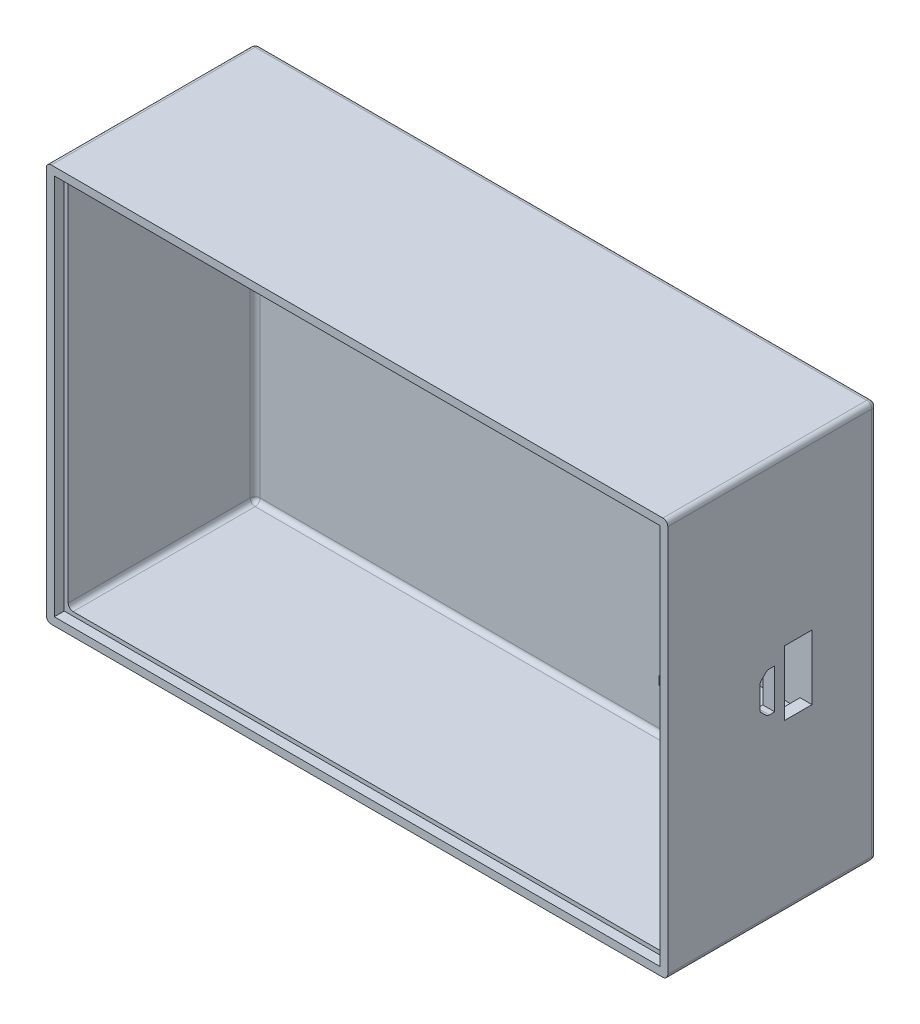
SolidWorks part; units mm, degrees
material "Резина"
ref_plane "Спереди" through (0, 0, 0) normal (0, 0, 1) x (1, 0, 0)
ref_plane "Сверху" through (0, 0, 0) normal (0, 1, 0) x (1, 0, 0)
ref_plane "Справа" through (0, 0, 0) normal (1, 0, 0) x (0, 0, -1)
sketch "Эскиз1" plane through (0, 0, 0) normal (0, 0, 1) x (1, 0, 0)
  line L1 (-62.5, 40) -> (62.5, 40)
  line L2 (-62.5, 40) -> (-62.5, -40)
  line L3 (-62.5, -40) -> (62.5, -40)
  line L4 (62.5, 40) -> (62.5, -40)
  line L5 (-62.5, 40) -> (62.5, -40) construction
  line L6 (-62.5, -40) -> (62.5, 40) construction
  point P0 (0, 0)
  dimension "D1" = 125
  dimension "D2" = 80
extrude "Бобышка-Вытянуть1" add sketch "Эскиз1" along normal blind 40
sketch "Эскиз2" plane through (0, 0, 40) normal (0, 0, 1) x (1, 0, 0)
  line L0 (62.5, 40) -> (-62.5, 40) construction
  line L1 (-60.1, 37.6) -> (60.1, 37.6)
  line L2 (-60.1, 37.6) -> (-60.1, -37.6)
  line L3 (-60.1, -37.6) -> (60.1, -37.6)
  line L4 (60.1, 37.6) -> (60.1, -37.6)
  line L5 (-60.1, 37.6) -> (60.1, -37.6) construction
  line L6 (-60.1, -37.6) -> (60.1, 37.6) construction
  line L7 (62.5, -40) -> (62.5, 40) construction
  point P0 (0, 0)
  dimension "D1" = 2.4
  dimension "D2" = 2.4
extrude "Вырез-Вытянуть1" cut sketch "Эскиз2" against normal blind 37.6
fillet "Скругление1" radius 1 8 edges at (62.5, -40, 20) (62.5, 40, 20) (62.5, 0, 0) (0, 40, 0) (-62.5, 40, 20) (-62.5, -40, 20) (0, -40, 0) (-62.5, 0, 0)
fillet "Скругление2" radius 1 8 edges at (60.1, 37.6, 21.2) (60.1, 0, 2.4) (60.1, -37.6, 21.2) (0, 37.6, 2.4) (-60.1, 37.6, 21.2) (0, -37.6, 2.4) (-60.1, -37.6, 21.2) (-60.1, 0, 2.4)
sketch "Эскиз3" plane through (0, 0, 0) normal (0, 0, -1) x (-1, 0, 0)
  line L0 (-61.5, 5) -> (59.5, 5) construction
  line L4 (-61.5, 39) -> (-61.5, -39) construction
  text T0 "Для\r\nЗСУ" font "Times New Roman" height 20
  dimension "D1" = 5
extrude "Вырез-Вытянуть2" cut sketch "Эскиз3" against normal blind 0.5
sketch "Эскиз4" plane through (62.5, 0, 0) normal (1, 0, 0) x (0, 0, -1)
  line L0 (0, 0) -> (-20.5, 0) construction
  line L1 (-20.5, -4) -> (-20.5, 4)
  line L2 (-20.5, 4) -> (-21.5858, 4)
  line L3 (-23.5, 2.0858) -> (-23.5, -2.0858)
  line L4 (-15.75, 0) -> (-20.5, 0) construction
  line L5 (-13, 6.5) -> (-18.5, 6.5)
  line L6 (-13, 6.5) -> (-13, -6.5)
  line L7 (-13, -6.5) -> (-18.5, -6.5)
  line L8 (-18.5, 6.5) -> (-18.5, -6.5)
  line L9 (-13, 6.5) -> (-18.5, -6.5) construction
  line L10 (-13, -6.5) -> (-18.5, 6.5) construction
  line L11 (-22.2929, 3.7071) -> (-23.2071, 2.7929)
  line L12 (-22.2929, -3.7071) -> (-23.2071, -2.7929)
  line L13 (-20.5, -4) -> (-21.5858, -4)
  arc A0 (-22.2929, -3.7071) -> (-21.5858, -4) centre (-21.5858, -3) ccw
  arc A1 (-23.2071, -2.7929) -> (-23.5, -2.0858) centre (-22.5, -2.0858) cw
  arc A2 (-23.2071, 2.7929) -> (-23.5, 2.0858) centre (-22.5, 2.0858) ccw
  arc A3 (-22.2929, 3.7071) -> (-21.5858, 4) centre (-21.5858, 3) cw
  point P5 (-15.75, 0)
  point P15 (-23.5, 0)
  point P18 (-22, -4)
  point P21 (-23.5, -2.5)
  point P24 (-23.5, 2.5)
  point P27 (-22, 4)
  dimension "D9" = 1
  dimension "D1" = 13
  dimension "D2" = 5.5
  dimension "D3" = 13
  dimension "D4" = 2
  dimension "D5" = 3
  dimension "D6" = 8
  dimension "D7" = 1.5
  dimension "D8" = 1.5
extrude "Вырез-Вытянуть3" cut sketch "Эскиз4" against normal blind 5
sketch "Эскиз5" plane through (60.1, 0, 0) normal (-1, 0, 0) x (0, 0, 1)
  line L0 (11.4, 0) -> (29.8169, 0) construction
  line L1 (11.4, 0) -> (11.4, -8.5)
  line L2 (11.4, -8.5) -> (13, -8.5)
  line L3 (13, -8.5) -> (13, 8.5)
  line L4 (11.4, 0) -> (11.4, 8.5)
  line L5 (11.4, 8.5) -> (13, 8.5)
  line L13 (0, -39) -> (0, 39) construction
  line L15 (11.4, -8.5) -> (21.4, -8.5)
  line L16 (11.4, -8.5) -> (11.4, -10.1)
  line L17 (11.4, -10.1) -> (21.4, -10.1)
  line L18 (21.4, -8.5) -> (21.4, -10.1)
  line L19 (11.4, -8.5) -> (21.4, -10.1) construction
  line L20 (11.4, -10.1) -> (21.4, -8.5) construction
  point P8 (16.4, -9.3)
  line M18 (18.5, 6.5) -> (18.5, -6.5)
  dimension "D1" = 1.6
  dimension "D2" = 17
  dimension "D3" = 8.5
  dimension "D4" = 13
  dimension "D5" = 17
  dimension "D6" = 1.6
  dimension "D7" = 10
  dimension "D8" = 11.4
extrude "Бобышка-Вытянуть2" add sketch "Эскиз5" along normal blind 20 contours L0 L1 L2 L3 M18 | L18 L15 L2 L16 L17
sketch "Эскиз6" plane through (0, 0, 13) normal (0, 0, 1) x (1, 0, 0)
  line L0 (40.1, 0) -> (43.5026, 0) construction
  line L1 (40.1, -8.5) -> (40.1, 8.5) construction
  line L2 (40.1, 8.5) -> (60.1, 8.5) construction
  line L3 (43.6526, -1.5) -> (43.3526, -1.5)
  line L4 (43.9026, -1.25) -> (43.9026, 1.25)
  line L5 (43.6526, 1.5) -> (43.3526, 1.5)
  line L6 (43.1026, -1.25) -> (43.1026, 1.25)
  line L7 (43.9026, -1.5) -> (43.1026, 1.5) construction
  line L8 (43.9026, 1.5) -> (43.1026, -1.5) construction
  line L9 (45.9832, 6.5) -> (43.9832, 6.5)
  line L10 (46.2332, 6.75) -> (46.2332, 7.05)
  line L11 (45.9832, 7.3) -> (43.9832, 7.3)
  line L12 (43.7332, 6.75) -> (43.7332, 7.05)
  line L13 (46.2332, 6.5) -> (43.7332, 7.3) construction
  line L14 (46.2332, 7.3) -> (43.7332, 6.5) construction
  arc A0 (43.9026, 1.25) -> (43.6526, 1.5) centre (43.6526, 1.25) ccw
  arc A1 (43.1026, 1.25) -> (43.3526, 1.5) centre (43.3526, 1.25) cw
  arc A2 (43.3526, -1.5) -> (43.1026, -1.25) centre (43.3526, -1.25) cw
  arc A3 (43.9026, -1.25) -> (43.6526, -1.5) centre (43.6526, -1.25) cw
  arc A4 (43.7332, 7.05) -> (43.9832, 7.3) centre (43.9832, 7.05) cw
  arc A5 (43.9832, 6.5) -> (43.7332, 6.75) centre (43.9832, 6.75) cw
  arc A6 (46.2332, 7.05) -> (45.9832, 7.3) centre (45.9832, 7.05) ccw
  arc A7 (46.2332, 6.75) -> (45.9832, 6.5) centre (45.9832, 6.75) cw
  point P8 (44.9832, 6.9)
  point P15 (44.9832, 7.3)
  dimension "D7" = 0.25
  dimension "D8" = 0.25
  dimension "D1" = 0.8
  dimension "D2" = 3
  dimension "D3" = 8.5
  dimension "D4" = 0.8
  dimension "D5" = 2.5
  dimension "D6" = 1.2
extrude "Бобышка-Вытянуть3" add sketch "Эскиз6" along normal blind 8
sketch "Эскиз7" plane through (0, 0, 40) normal (0, 0, 1) x (1, 0, 0)
  line L4 (60.9, -38.4) -> (60.9, 38.4)
  line L5 (60.9, 38.4) -> (-60.9, 38.4)
  line L6 (-60.9, 38.4) -> (-60.9, -38.4)
  line L7 (-60.9, -38.4) -> (60.9, -38.4)
  line L8 (-61.5, -40) -> (61.5, -40)
  line L9 (62.5, -39) -> (62.5, 39)
  line L10 (61.5, 40) -> (-61.5, 40)
  line L11 (-62.5, 39) -> (-62.5, -39)
  line L12 (-61.5, -40) -> (61.5, -40)
  line L13 (62.5, -39) -> (62.5, 39)
  line L14 (61.5, 40) -> (-61.5, 40)
  line L15 (-62.5, 39) -> (-62.5, -39)
  arc A4 (60.9, 38.4) -> (60.9, 38.4) centre (60.9, 38.4) ccw
  arc A5 (-60.9, 38.4) -> (-60.9, 38.4) centre (-60.9, 38.4) ccw
  arc A6 (-60.9, -38.4) -> (-60.9, -38.4) centre (-60.9, -38.4) ccw
  arc A7 (60.9, -38.4) -> (60.9, -38.4) centre (60.9, -38.4) ccw
  arc A8 (61.5, -40) -> (62.5, -39) centre (61.5, -39) ccw
  arc A9 (62.5, 39) -> (61.5, 40) centre (61.5, 39) ccw
  arc A10 (-61.5, 40) -> (-62.5, 39) centre (-61.5, 39) ccw
  arc A11 (-62.5, -39) -> (-61.5, -40) centre (-61.5, -39) ccw
  arc A12 (61.5, -40) -> (62.5, -39) centre (61.5, -39) ccw
  arc A13 (62.5, 39) -> (61.5, 40) centre (61.5, 39) ccw
  arc A14 (-61.5, 40) -> (-62.5, 39) centre (-61.5, 39) ccw
  arc A15 (-62.5, -39) -> (-61.5, -40) centre (-61.5, -39) ccw
  dimension "D1" = 0
  dimension "D2" = 1.6
extrude "Бобышка-Вытянуть4" add sketch "Эскиз7" along normal blind 2
